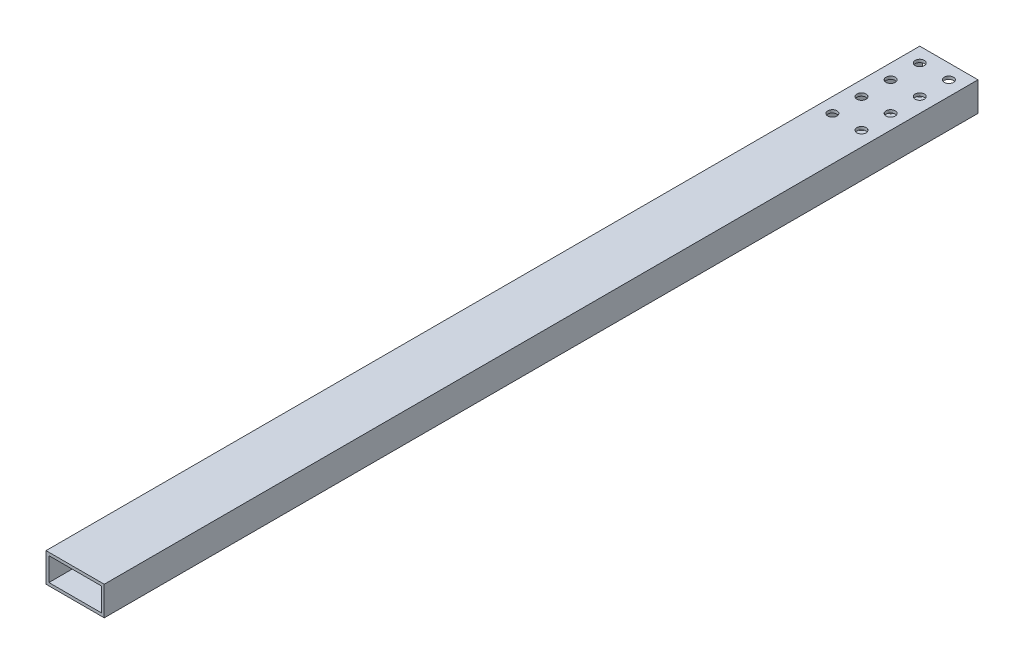
SolidWorks part; units mm, degrees
ref_plane "前视基准面" through (0, 0, 0) normal (0, 0, 1) x (1, 0, 0)
ref_plane "上视基准面" through (0, 0, 0) normal (0, 1, 0) x (1, 0, 0)
ref_plane "右视基准面" through (0, 0, 0) normal (1, 0, 0) x (0, 0, -1)
other "Configuration Table"
sketch "草图1" plane through (0, 0, 0) normal (0, 0, 1) x (1, 0, 0)
  line L1 (0, 0) -> (20, 0)
  line L2 (0, 0) -> (0, -10)
  line L3 (0, -10) -> (20, -10)
  line L4 (20, 0) -> (20, -10)
  dimension "D1" = 20
  dimension "D2" = 10
extrude "拉伸-薄壁1" add sketch "草图1" along normal blind 300 thin
sketch "草图2" plane through (0, 0, 0) normal (0, 1, 0) x (1, 0, 0)
  line L0 (0, -10) -> (20, -10) construction
  line L1 (0, -300) -> (0, 0) construction
  line L2 (20, -300) -> (20, 0) construction
  line L3 (20, 0) -> (0, 0) construction
  line L4 (10, 0) -> (10, -10) construction
  line L5 (0, -20) -> (20, -20) construction
  circle A0 centre (15, -5) radius 1.575
  circle A1 centre (5, -5) radius 1.575
  circle A2 centre (5, -15) radius 1.575
  circle A3 centre (15, -15) radius 1.575
  circle A4 centre (15, -25) radius 1.575
  circle A5 centre (5, -25) radius 1.575
  circle A6 centre (5, -35) radius 1.575
  circle A7 centre (15, -35) radius 1.575
  dimension "D2" = 3.15
  dimension "D1" = 10
  dimension "D3" = 5
  dimension "D4" = 5
  dimension "D5" = 20
extrude "切除-拉伸1" cut sketch "草图2" against normal through all
